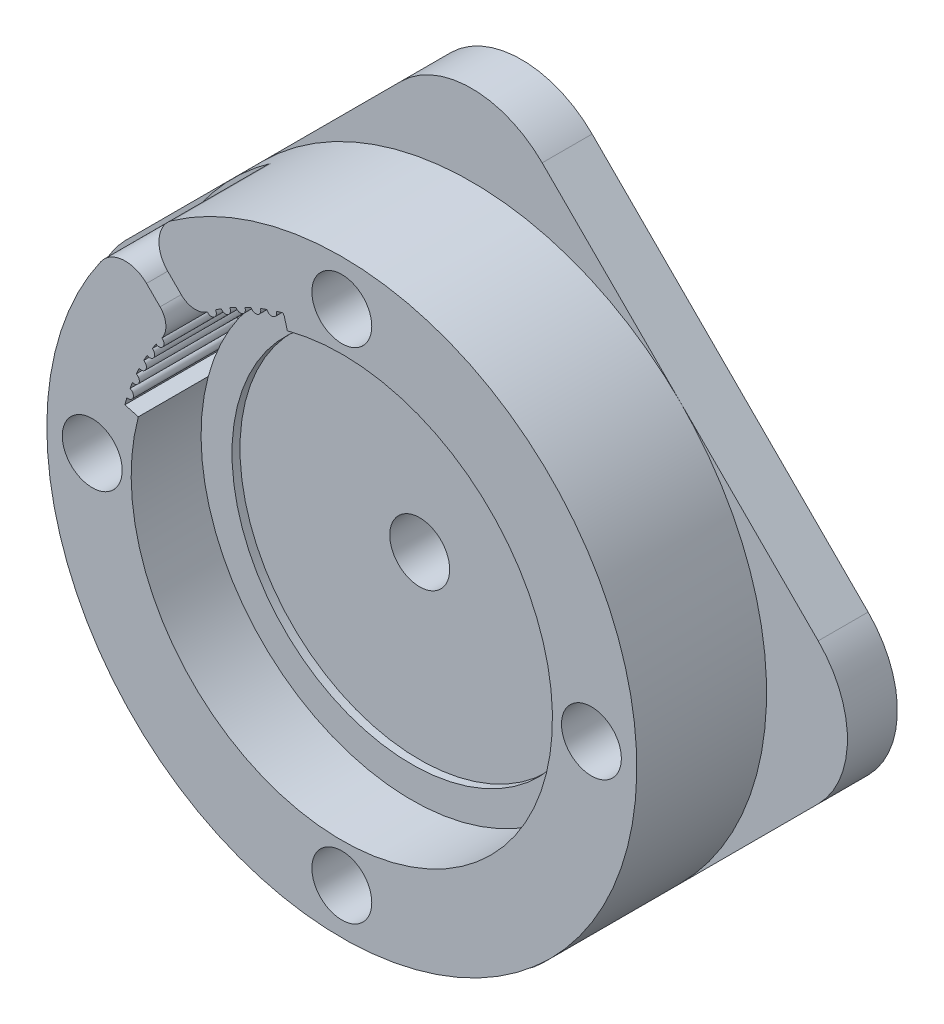
SolidWorks part; units mm, degrees
ref_plane "前视基准面" through (0, 0, 0) normal (0, 0, 1) x (1, 0, 0)
ref_plane "上视基准面" through (0, 0, 0) normal (0, 1, 0) x (1, 0, 0)
ref_plane "右视基准面" through (0, 0, 0) normal (1, 0, 0) x (0, 0, -1)
sketch "旋转草图同步带轮01" plane through (0, 0, 0) normal (1, 0, 0) x (0, 0, -1)
  line L0 (0, 0) -> (1, 0) construction
  line L1 (4.5, 0) -> (4.5, 30.3672)
  line L2 (4.5, 30.3672) -> (-4.5, 30.3672)
  line L3 (-4.5, 30.3672) -> (-4.5, 0)
  line L4 (-4.5, 0) -> (4.5, 0)
  dimension "GearBeltOutsideDiameter" = 30.3672
revolve "同步带轮01" add sketch "旋转草图同步带轮01" angle 360 about L0
sketch "齿草图同步带轮01" plane through (0, 0, 0) normal (0, 0, 1) x (1, 0, 0)
  line L0 (-0.8137, 30.3563) -> (0, 32.9072)
  line L1 (0, 32.9072) -> (0.8137, 30.3563)
  arc A0 (0.8137, 30.3563) -> (0.6, 30.1482) centre (0.8082, 30.1482) ccw
  arc A1 (0.6, 30.1482) -> (-0.6, 30.1482) centre (0, 30.1482) cw
  arc A2 (-0.6, 30.1482) -> (-0.8137, 30.3563) centre (-0.8082, 30.1482) ccw
  dimension "GearBeltToothR1" = 0.4163
  dimension "GearBeltToothR2" = 1.2
  dimension "GearBeltToothCapX1" = 0.8137
  dimension "GearBeltToothCapY1" = 2.5509
  dimension "GearBeltToothCapX2" = 0.8137
  dimension "GearBeltToothCapY2" = 2.5509
extrude "齿拉伸切除同步带轮01" cut sketch "齿草图同步带轮01" against normal blind 4.5 and the other way blind 4.5
sketch "孔旋转草图" plane through (0, 0, 0) normal (1, 0, 0) x (0, 0, -1)
  line L0 (0, 0) -> (1, 0) construction
  line L1 (-4.5, 0) -> (4.5, 0)
  line L2 (4.5, 0) -> (4.5, 0.0098)
  line L3 (4.5, 0.0098) -> (-4.5, 0.0098)
  line L4 (-4.5, 0.0098) -> (-4.5, 0)
  dimension "TaperSide1" = 0.0098
  dimension "TaperSide2" = 0.0098
revolve "孔旋转切除" cut sketch "孔旋转草图" angle 360 about L0
sketch "草图5" plane through (0, 0, -4.5) normal (0, 0, -1) x (-1, 0, 0)
  circle A0 centre (0, 0) radius 29.5482
  circle A1 centre (0, 0) radius 36.0242
extrude "切除-拉伸2" cut sketch "草图5" against normal blind 10
sketch "草图6" plane through (0, 0, -4.5) normal (0, 0, -1) x (-1, 0, 0)
  circle A1 centre (0, 0) radius 29.5482
  circle A2 centre (0, 0) radius 29.5482
  dimension "D1" = 0
extrude "凸台-拉伸1" add sketch "草图6" along normal blind 9
sketch "草图7" plane through (0, 0, 4.5) normal (0, 0, 1) x (1, 0, 0)
  circle A0 centre (0, 0) radius 21.1
  dimension "D1" = 42.2
extrude "切除-拉伸3" cut sketch "草图7" against normal blind 7
sketch "草图8" plane through (0, 0, 4.5) normal (0, 0, 1) x (1, 0, 0)
  circle A0 centre (0, 25) radius 1.6
  circle A1 centre (25, 0) radius 1.6
  circle A2 centre (0, -25) radius 1.6
  circle A3 centre (-25, 0) radius 1.6
  point P12 (0, 0)
  dimension "D1" = 3.2
  dimension "D2" = 25
  dimension "D3" = 4
extrude "切除-拉伸4" cut sketch "草图8" against normal blind 34
sketch "草图9" plane through (0, 0, -2.5) normal (0, 0, 1) x (1, 0, 0)
  circle A0 centre (0, 0) radius 3
  dimension "D1" = 6
extrude "切除-拉伸5" cut sketch "草图9" against normal blind 34
sketch "草图10" plane through (0, 0, -2.5) normal (0, 0, 1) x (1, 0, 0)
  circle A0 centre (0, 0) radius 18
  dimension "D1" = 36
extrude "切除-拉伸6" cut sketch "草图10" against normal blind 0.8
sketch "草图12" plane through (0, 0, 4.5) normal (0, 0, 1) x (1, 0, 0)
  circle A0 centre (0, -25) radius 3
  circle A1 centre (-25, 0) radius 3
  circle A2 centre (0, 25) radius 3
  circle A3 centre (25, 0) radius 3
  point P12 (0, 0)
  dimension "D1" = 6
  dimension "D2" = 4
extrude "切除-拉伸8" cut sketch "草图12" against normal blind 5
sketch "草图13" plane through (0, 0, -13.5) normal (0, 0, -1) x (-1, 0, 0)
  line L1 (7.0711, -34.7165) -> (34.7165, -7.0711)
  line L2 (-7.0711, -34.7165) -> (-34.7165, -7.0711)
  line L3 (-34.7165, 7.0711) -> (-7.0711, 34.7165)
  line L4 (34.7165, 7.0711) -> (7.0711, 34.7165)
  line L5 (0, -41.7875) -> (0, 41.7875) construction
  line L6 (-41.7875, 0) -> (41.7875, 0) construction
  arc A0 (-7.0711, -34.7165) -> (7.0711, -34.7165) centre (0, -27.6454) ccw
  arc A1 (34.7165, -7.0711) -> (34.7165, 7.0711) centre (27.6454, 0) ccw
  arc A2 (-7.0711, 34.7165) -> (7.0711, 34.7165) centre (0, 27.6454) cw
  arc A3 (-34.7165, -7.0711) -> (-34.7165, 7.0711) centre (-27.6454, 0) cw
  circle A6 centre (0, 0) radius 29.5482
  point P0 (0, 0)
  circle M7 centre (0, 0) radius 29.5482
  dimension "D1" = 10
extrude "凸台-拉伸2" add sketch "草图13" against normal blind 5 contours A2 L3 L4 M7 | A3 L2 L3 M7 | L2 A0 L1 M7 | L1 A1 L4 M7
sketch "草图14" plane through (0, 0, 4.5) normal (0, 0, 1) x (1, 0, 0)
  line L0 (-17.6777, 17.6777) -> (-26.6193, 26.6193) construction
  line L1 (-20.2844, 5.4352) -> (-21.7333, 5.8234)
  line L3 (-18.2071, 16.0858) -> (-23.6745, 21.5532)
  line L4 (-23.6745, 21.5532) -> (-21.5532, 23.6745)
  line L5 (-16.0858, 18.2071) -> (-21.5532, 23.6745)
  line L6 (-17.6777, 17.6777) -> (-21.5532, 23.6745) construction
  line L7 (-23.6745, 21.5532) -> (-17.6777, 17.6777) construction
  line L8 (-5.4352, 20.2844) -> (-5.8234, 21.7333)
  arc A0 (-18.6004, 12.6599) -> (-18.9854, 12.0749) centre (0, 0) ccw
  arc A2 (-5.4352, 20.2844) -> (-20.2844, 5.4352) centre (0, 0) ccw
  arc A3 (-5.8234, 21.7333) -> (-6.5484, 21.526) centre (0, 0) ccw
  arc A4 (-16.0858, 18.2071) -> (-13.4739, 18.0196) centre (-14.6716, 19.6213) ccw
  arc A5 (-18.2071, 16.0858) -> (-18.0196, 13.4739) centre (-19.6213, 14.6716) cw
  arc A6 (-13.4739, 18.0196) -> (-12.6599, 18.6004) centre (-13.0701, 18.3145) ccw
  arc A7 (-12.0749, 18.9854) -> (-11.2195, 19.5032) centre (-11.6501, 19.249) ccw
  arc A8 (-10.607, 19.8429) -> (-9.7149, 20.2946) centre (-10.1635, 20.0737) ccw
  arc A9 (-9.0786, 20.5871) -> (-8.155, 20.9701) centre (-8.6189, 20.7838) ccw
  arc A10 (-7.4984, 21.2138) -> (-6.5484, 21.526) centre (-7.0251, 21.3752) ccw
  arc A11 (-5.8753, 21.7194) -> (-5.7639, 21.5112) centre (-5.3912, 21.8446) ccw
  arc A12 (-7.4984, 21.2138) -> (-8.155, 20.9701) centre (0, 0) ccw
  arc A13 (-9.0786, 20.5871) -> (-9.7149, 20.2946) centre (0, 0) ccw
  arc A14 (-10.607, 19.8429) -> (-11.2195, 19.5032) centre (0, 0) ccw
  arc A15 (-12.0749, 18.9854) -> (-12.6599, 18.6004) centre (0, 0) ccw
  arc A16 (-21.2138, 7.4984) -> (-21.526, 6.5484) centre (-21.3752, 7.0251) cw
  arc A17 (-20.5871, 9.0786) -> (-20.9701, 8.155) centre (-20.7838, 8.6189) cw
  arc A18 (-19.8429, 10.607) -> (-20.2946, 9.7149) centre (-20.0737, 10.1635) cw
  arc A19 (-18.9854, 12.0749) -> (-19.5032, 11.2195) centre (-19.249, 11.6501) cw
  arc A20 (-18.0196, 13.4739) -> (-18.6004, 12.6599) centre (-18.3145, 13.0701) cw
  arc A21 (-21.526, 6.5484) -> (-21.7333, 5.8234) centre (0, 0) ccw
  arc A22 (-20.9701, 8.155) -> (-21.2138, 7.4984) centre (0, 0) ccw
  arc A23 (-20.2946, 9.7149) -> (-20.5871, 9.0786) centre (0, 0) ccw
  arc A24 (-19.5032, 11.2195) -> (-19.8429, 10.607) centre (0, 0) ccw
  point P6 (-17.6777, 17.6777)
  point P21 (-16.9352, 14.8138)
  point P42 (0, 0)
  dimension "D1" = 3
  dimension "D2" = 45
  dimension "D5" = 2
  dimension "D6" = 1
  dimension "D3" = 30
  dimension "D4" = 30
  dimension "D7" = 6
extrude "切除-拉伸9" cut sketch "草图14" against normal blind 10 contours A19 A24 A18 A23 A17 A22 A16 A21 L1 A0 L8 A11 A3 A10 A12 A9 A13 A8 A14 A7 A15 A6 A4 L5 A2 L3 A5 A20 | A2 L5 L4 L3
fillet "圆角1" radius 3 2 edges at (-21.9275, 19.8062, -0.5) (-19.8062, 21.9275, -0.5)
